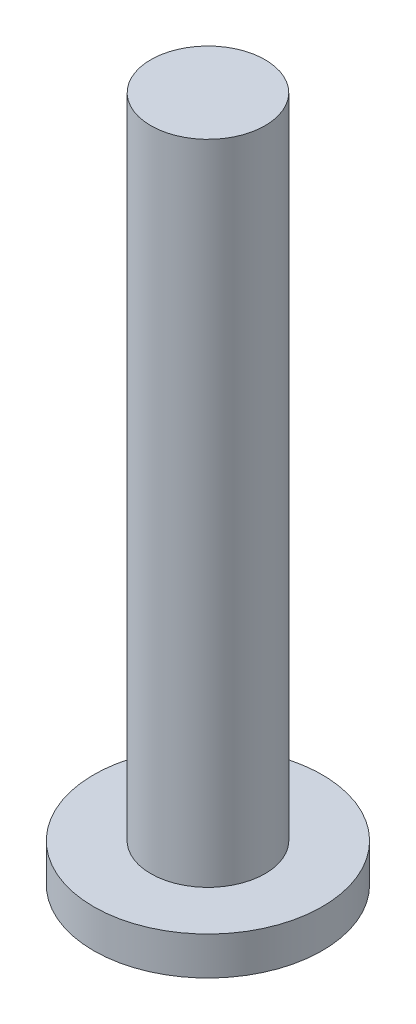
SolidWorks part; units mm, degrees
ref_plane "Спереди" through (0, 0, 0) normal (0, 0, 1) x (1, 0, 0)
ref_plane "Сверху" through (0, 0, 0) normal (0, 1, 0) x (1, 0, 0)
ref_plane "Справа" through (0, 0, 0) normal (1, 0, 0) x (0, 0, -1)
sketch "Эскиз1" plane through (0, 0, 0) normal (0, 1, 0) x (1, 0, 0)
  circle A0 centre (0, 0) radius 30
  dimension "D1" = 60
extrude "Бобышка-Вытянуть1" add sketch "Эскиз1" along normal blind 10
sketch "Эскиз2" plane through (0, 10, 0) normal (0, 1, 0) x (1, 0, 0)
  circle A0 centre (0, 0) radius 15
  dimension "D1" = 30
extrude "Бобышка-Вытянуть2" add sketch "Эскиз2" along normal blind 170
